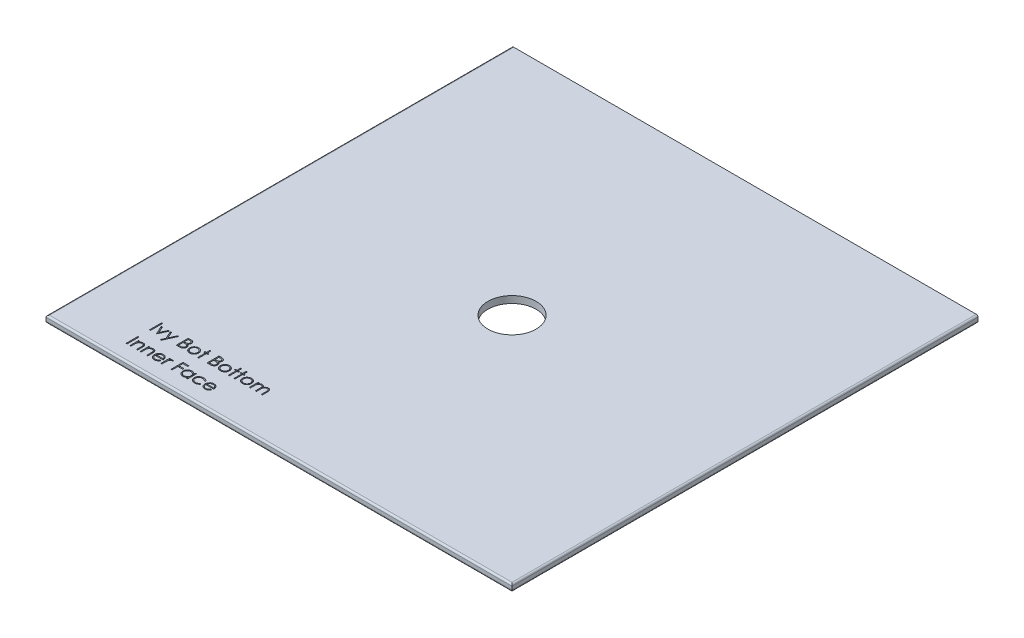
SolidWorks part; units mm, degrees
ref_plane "Front Plane" through (0, 0, 0) normal (0, 0, 1) x (1, 0, 0)
ref_plane "Top Plane" through (0, 0, 0) normal (0, 1, 0) x (1, 0, 0)
ref_plane "Right Plane" through (0, 0, 0) normal (1, 0, 0) x (0, 0, -1)
sketch "Sketch1" plane through (0, 0, 0) normal (0, 1, 0) x (1, 0, 0)
  line L1 (-67.7, 67.7) -> (67.7, 67.7)
  line L2 (-67.7, 67.7) -> (-67.7, -67.7)
  line L3 (-67.7, -67.7) -> (67.7, -67.7)
  line L4 (67.7, 67.7) -> (67.7, -67.7)
  point P4 (0, -67.7)
  point P6 (-67.7, 0)
  dimension "D1" = 135.4
  dimension "D2" = 135.4
extrude "Boss-Extrude1" add sketch "Sketch1" along normal blind 2 contours L1 L4 L3 L2
sketch "Sketch6" plane through (0, 2, 0) normal (0, 1, 0) x (1, 0, 0)
  circle A0 centre (0, 0) radius 7
  dimension "D1" = 14
extrude "Cut-Extrude1" cut sketch "Sketch6" against normal through all contours A0
fillet "Fillet1" radius 0.5 7 edges at (-67.7, 0, 0) (0, 0, -67.7) (0, 0, 67.7) (67.7, 0, 0) (67.7, 2, 0) (-67.7, 2, 0) (0, 2, 67.7)
sketch "Sketch9" plane through (0, 2, 0) normal (0, 1, 0) x (1, 0, 0)
  text T0 "Ivy Bot Bottom\r\nInner Face"
extrude "Cut-Extrude4" cut sketch "Sketch9" against normal blind 1
sketch "Sketch10" plane through (0, 0, 0) normal (0, -1, 0) x (1, 0, 0)
  line L0 (-12.9733, 25) -> (12.9733, 25) construction
  line L1 (-12.9733, -25) -> (12.9733, -25) construction
  text T0 "3               1"
  text T1 " 2               4"
  point P8 (0, 25)
  point P12 (0, -25)
  dimension "D1" = 25
  dimension "D2" = 25
extrude "Cut-Extrude5" cut sketch "Sketch10" against normal blind 1
sketch "Sketch11" plane through (0, 0, 0) normal (0, -1, 0) x (1, 0, 0)
  line L0 (0, 67.2) -> (0, -67.2) construction
  line L1 (67.2, 67.2) -> (-67.2, 67.2) construction
  line L2 (-67.2, -67.2) -> (67.2, -67.2) construction
  line L3 (-67.2, 0) -> (67.2, 0) construction
  line L4 (67.2, -67.2) -> (67.2, 67.2) construction
  line L5 (50, 0) -> (-50, 0) construction
  circle A0 centre (-50, 0) radius 2.5
  circle A1 centre (50, 0) radius 2.5
  point P13 (0, 0)
  point P17 (0, 0)
extrude "Boss-Extrude2" add sketch "Sketch11" along normal blind 10
fillet "Fillet4" radius 2 2 edges at (50, -10, 2.5) (-50, -10, -2.5)
